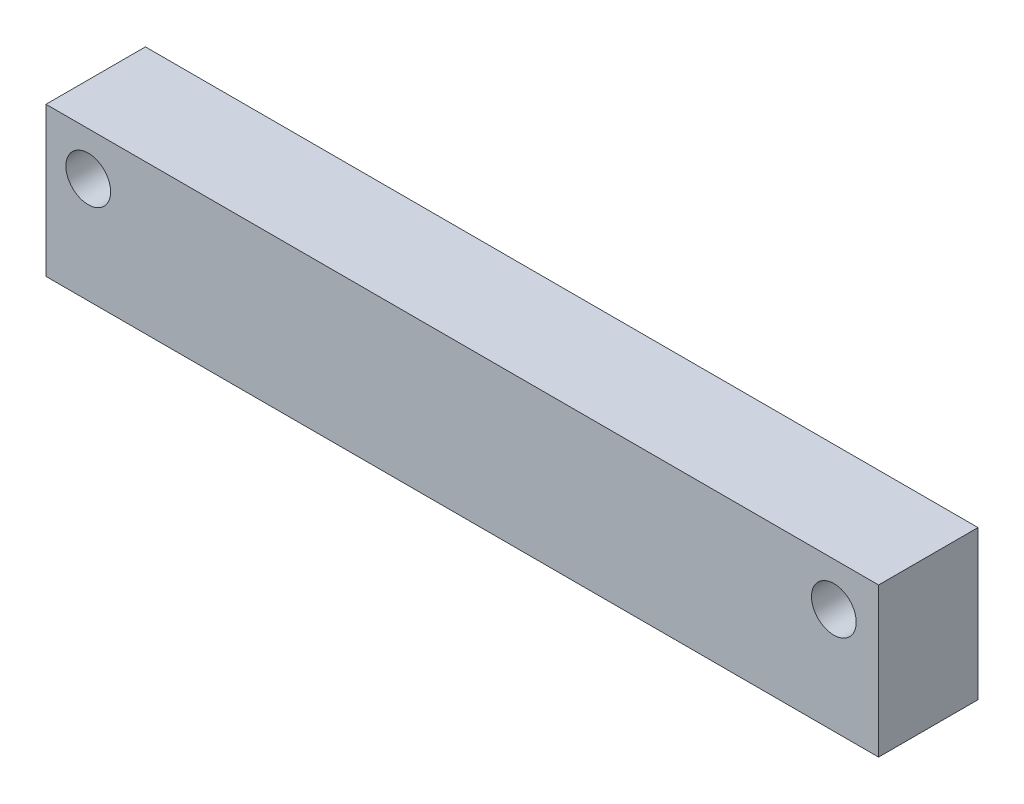
SolidWorks part; units mm, degrees
ref_plane "Front Plane" through (0, 0, 0) normal (0, 0, 1) x (1, 0, 0)
ref_plane "Top Plane" through (0, 0, 0) normal (0, 1, 0) x (1, 0, 0)
ref_plane "Right Plane" through (0, 0, 0) normal (1, 0, 0) x (0, 0, -1)
sketch "Sketch2" plane through (0, 0, 0) normal (0, 0, 1) x (1, 0, 0)
  line L0 (121.05, 58.4) -> (121.05, 32.9268) construction
  line L1 (80.65, 32.9268) -> (80.65, 58.4) construction
  line L2 (121.05, 58.4) -> (121.05, 32.9268)
  line L3 (80.65, 32.9268) -> (80.65, 58.4)
  line L4 (67.35, 50.5) -> (67.35, 38.5)
  line L5 (67.35, 38.5) -> (134.35, 38.5)
  line L6 (134.35, 38.5) -> (134.35, 50.5)
  line L7 (134.35, 50.5) -> (67.35, 50.5)
  line L8 (100.85, 50.5) -> (100.85, 38.5) construction
  line L9 (80.65, 45.6634) -> (121.05, 45.6634) construction
  line L10 (70.75, 48.5) -> (70.75, 40.5) construction
  circle A0 centre (70.75, 47) radius 1.5 construction
  circle A1 centre (70.75, 42) radius 1.5 construction
  point P12 (100.85, 45.6634)
  point P20 (70.75, 44.5)
  point P21 (100.85, 44.5)
  dimension "D1" = 12
  dimension "D2" = 67
extrude "Boss-Extrude1" add sketch "Sketch2" along normal up to surface (8 mm away) contours L3 L7 L4 L5 | L2 L7 L3 L5 | L6 L7 L2 L5
hole_wizard "M3 Clearance Hole1" positions "Sketch5" profile "Sketch4" hole size "M3" standard "ANSI Metric" end condition through all
sketch "Sketch5" plane through (0, 0, 8) normal (0, 0, 1) x (1, 0, 0)
  point P0 (70.75, 47)
  point P12 (130.75, 47)
sketch "Sketch4" plane through (70.75, 47, 8) normal (0, 1, 0) x (1, 0, 0)
  line L0 (0, 0) -> (0, 8)
  line L1 (0, 8) -> (1.8, 8)
  line L2 (1.8, 8) -> (1.8, 0)
  line L5 (1.8, 0) -> (0, 0)
  line L11 (0, -6.35) -> (0, 107.95) construction
  dimension "Thru Hole Dia." = 3.6
  dimension "Thru Hole Depth" = 8
